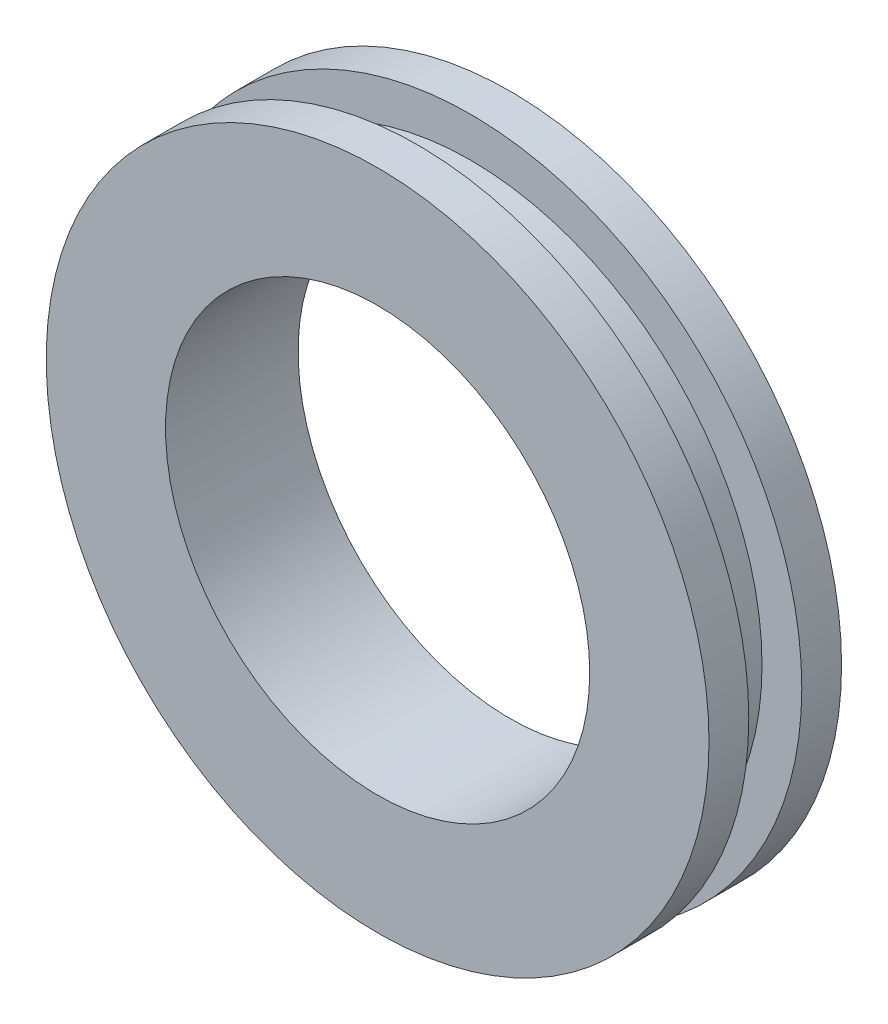
SolidWorks part; units mm, degrees
material "AISI 1020"
ref_plane "Alzado" through (0, 0, 0) normal (0, 0, 1) x (1, 0, 0)
ref_plane "Planta" through (0, 0, 0) normal (0, 1, 0) x (1, 0, 0)
ref_plane "Vista lateral" through (0, 0, 0) normal (1, 0, 0) x (0, 0, -1)
sketch "Croquis1" plane through (0, 0, 0) normal (1, 0, 0) x (0, 0, -1)
  line L0 (-17.6913, 0) -> (16.9345, 0) construction
  line L1 (-2.5, 8) -> (2.5, 8)
  line L2 (2.5, 8) -> (2.5, 12.5)
  line L3 (2.5, 12.5) -> (1, 12.5)
  line L4 (1, 12.5) -> (1, 11)
  line L5 (1, 11) -> (-1, 11)
  line L6 (-1, 11) -> (-1, 12.5)
  line L7 (-1, 12.5) -> (-2.5, 12.5)
  line L8 (-2.5, 12.5) -> (-2.5, 8)
  point P10 (0, 11)
  point P12 (0, 8)
  point P13 (-4.9474, 8)
  point P14 (-1.4853, 11.0293)
  point P15 (0, 0)
  point P16 (-1.75, 12.5)
  dimension "D1" = 16
  dimension "D2" = 5
  dimension "D3" = 1.5
  dimension "D4" = 25
revolve "Revolución1" add sketch "Croquis1" angle 360 about L0
